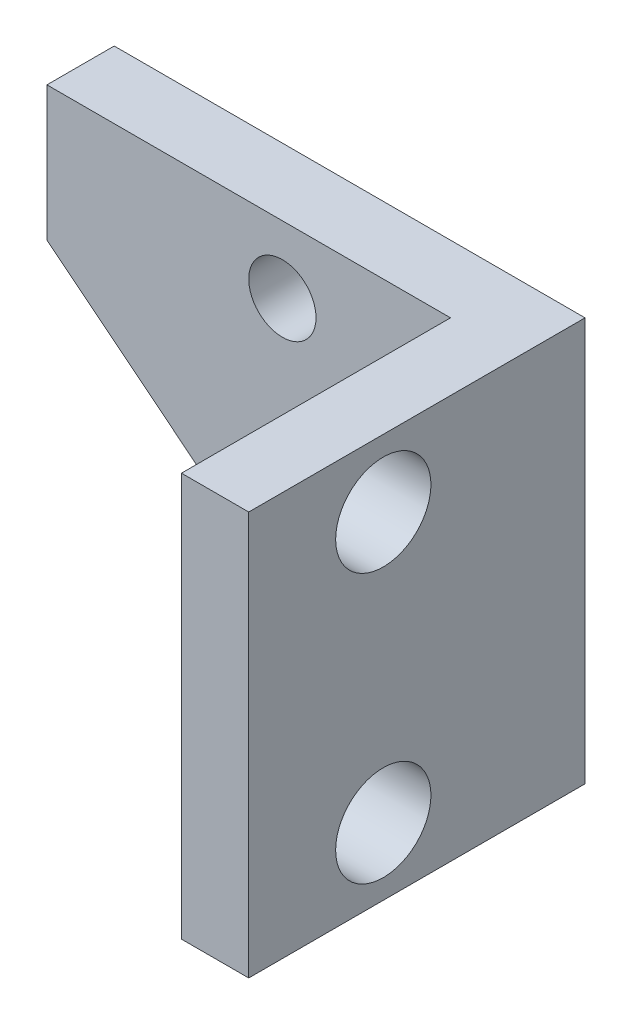
SolidWorks part; units mm, degrees
ref_plane "Front Plane" through (0, 0, 0) normal (0, 0, 1) x (1, 0, 0)
ref_plane "Top Plane" through (0, 0, 0) normal (0, 1, 0) x (1, 0, 0)
ref_plane "Right Plane" through (0, 0, 0) normal (1, 0, 0) x (0, 0, -1)
sketch "Sketch1" plane through (0, 0, 0) normal (0, 0, 1) x (1, 0, 0)
  line L0 (0, 0) -> (-22.225, 0)
  line L1 (-22.225, 0) -> (-22.225, -6.35)
  line L2 (-22.225, -6.35) -> (-6.35, -19.05)
  line L3 (-6.35, -19.05) -> (0, -19.05)
  line L4 (0, -19.05) -> (0, 0)
  point P3 (-4.9441, 0)
  point P7 (-2.0024, -7.0083)
  point P8 (-6.0071, -3.1637)
  dimension "D1" = 6.35
  dimension "D2" = 19.05
  dimension "D3" = 22.225
extrude "Boss-Extrude1" add sketch "Sketch1" along normal blind 3.175
hole_wizard "1/8 (0.1250) Dowel Hole2" positions "Sketch5" profile "Sketch6" hole size "1/8" standard "ANSI Inch" end condition through all
sketch "Sketch5" plane through (0, 0, 3.175) normal (0, 0, 1) x (1, 0, 0)
  line L0 (-22.225, -3.175) -> (0, -3.175) construction
  line L1 (-22.225, 0) -> (-22.225, -6.35) construction
  line L2 (0, -19.05) -> (0, 0) construction
  point P10 (-11.1125, -3.175)
sketch "Sketch6" plane through (-11.1125, -3.175, 3.175) normal (1, 0, 0) x (0, -1, 0)
  line L0 (0, 0) -> (0, 3.175)
  line L1 (0, 3.175) -> (1.5875, 3.175)
  line L2 (1.5875, 3.175) -> (1.5875, 0)
  line L5 (1.5875, 0) -> (0, 0)
  line L11 (0, -6.35) -> (0, 107.95) construction
  dimension "Thru Hole Dia." = 3.175
  dimension "Thru Hole Depth" = 3.175
sketch "Sketch7" plane through (0, 0, 3.175) normal (0, 0, 1) x (1, 0, 0)
  line L0 (-6.35, -19.05) -> (0, -19.05) construction
  line L1 (0, 0) -> (-3.175, 0)
  line L2 (0, 0) -> (0, -19.05)
  line L3 (0, -19.05) -> (-3.175, -19.05)
  line L4 (-3.175, 0) -> (-3.175, -19.05)
extrude "Boss-Extrude2" add sketch "Sketch7" along normal blind 15.875 from surface at -3.175 starting at face at (-9.525, -3.175, 0)
hole_wizard "#8 Clearance Hole1" positions "Sketch8" profile "Sketch9" hole size "#8" standard "ANSI Inch" end condition through all
sketch "Sketch8" plane through (-3.175, 0, 0) normal (-1, 0, 0) x (0, 0, 1)
  line L0 (9.525, 0) -> (9.525, -3.175) construction
  line L1 (15.875, 0) -> (3.175, 0) construction
  line L2 (9.525, -3.175) -> (9.525, -15.875) construction
  line L3 (9.525, -15.875) -> (9.525, -19.05) construction
  line L4 (15.875, -19.05) -> (3.175, -19.05) construction
  point P2 (9.525, -3.175)
  point P6 (9.525, -15.875)
  dimension "D1" = 3.175
sketch "Sketch9" plane through (-3.175, -15.875, 9.525) normal (0, 1, 0) x (0, 0, 1)
  line L0 (0, 0) -> (0, 3.175)
  line L1 (0, 3.175) -> (2.2479, 3.175)
  line L2 (2.2479, 3.175) -> (2.2479, 0)
  line L5 (2.2479, 0) -> (0, 0)
  line L11 (0, -6.35) -> (0, 107.95) construction
  dimension "Thru Hole Dia." = 4.4958
  dimension "Thru Hole Depth" = 3.175
